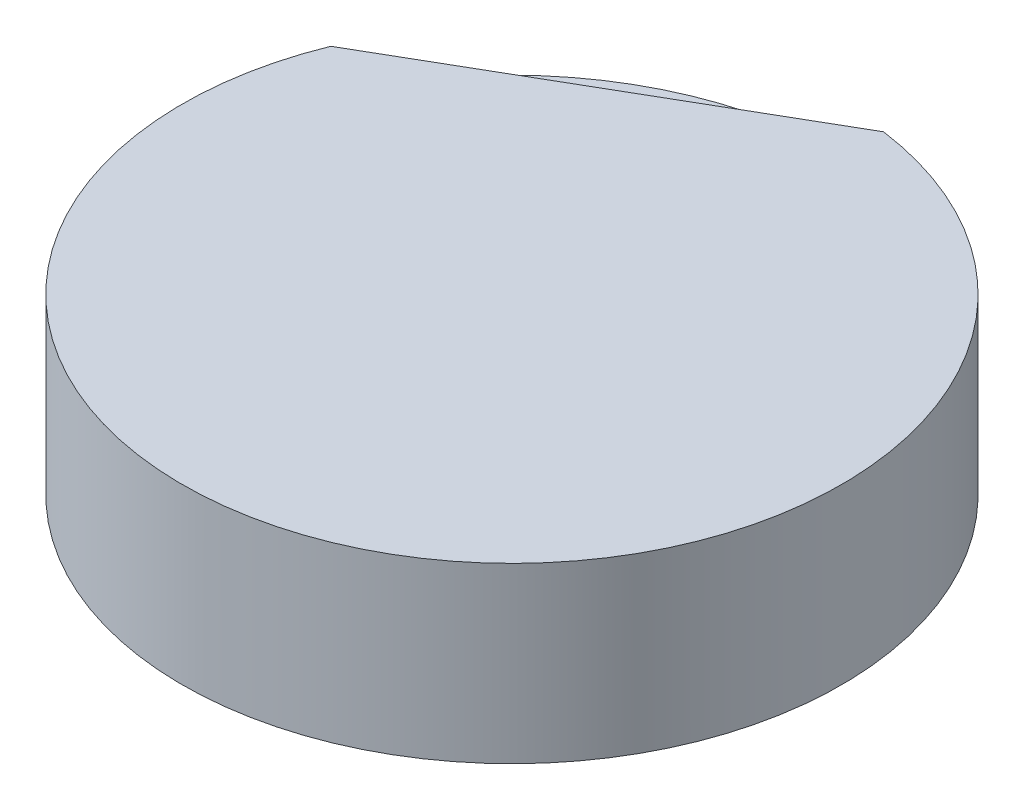
SolidWorks part; units mm, degrees
other "Fixed Steel Cup Liner 3"
ref_plane "Front Plane" through (0, 0, 0) normal (0, 0, 1) x (1, 0, 0)
ref_plane "Top Plane" through (0, 0, 0) normal (0, 1, 0) x (1, 0, 0)
ref_plane "Right Plane" through (0, 0, 0) normal (1, 0, 0) x (0, 0, -1)
sketch3d "Keyed Back Sketch datum points"
  point P0 (-56.2917, -69, 0)
  point P1 (-46.2917, -69, 0)
  point P2 (-56.2917, -69, 10)
ref_plane "Keyed Back Sketch plane" through (0, -69, 0) normal (0, -1, 0) x (-1, 0, 0)
sketch "Keyed Back Sketch" plane through (0, -69, 0) normal (0, -1, 0) x (-1, 0, 0)
  line L0 (74.8116, 27.4126) -> (70.7718, 29.745)
  arc A0 (70.7718, 29.745) -> (74.8116, 27.4126) centre (71.2917, 25.9808) ccw
extrude "Keyed Back" add sketch "Keyed Back Sketch" along normal blind 0.5 separate body
sketch3d "Cup Blank Sketch datum points"
  point P0 (-56.2917, -69.5, 0)
  point P1 (-46.2917, -69.5, 0)
  point P2 (-56.2917, -69.5, 10)
ref_plane "Cup Blank Sketch plane" through (0, -69.5, 0) normal (0, -1, 0) x (-1, 0, 0)
sketch "Cup Blank Sketch" plane through (0, -69.5, 0) normal (0, -1, 0) x (-1, 0, 0)
  circle A0 centre (71.2917, 25.9808) radius 3.8
extrude "Cup Blank" add sketch "Cup Blank Sketch" along normal blind 1.5
sketch3d "Spherical Bearing Seat axis line"
  line L0 (-71.2917, -73, -35.9808) -> (-71.2917, -73, -15.9808) construction
ref_axis "Spherical Bearing Seat axis" through (-71.2917, -73, -35.9808) along (0, 0, 1)
sketch3d "Spherical Bearing Seat profile datum points"
  point P0 (-71.2917, -73, -25.9808)
  point P1 (-61.2917, -73, -25.9808)
  point P2 (-71.2917, -73, -15.9808)
ref_plane "Spherical Bearing Seat profile plane" through (0, -73, 0) normal (0, -1, 0) x (-1, 0, 0)
sketch "Spherical Bearing Seat profile" plane through (0, -73, 0) normal (0, -1, 0) x (-1, 0, 0)
  line L0 (71.2917, 22.8808) -> (71.2917, 29.0808)
  arc A0 (71.2917, 29.0808) -> (71.2917, 22.8808) centre (71.2917, 25.9808) ccw
revolve "Spherical Bearing Seat" cut sketch "Spherical Bearing Seat profile" angle 360 about axis through (-71.2917, -73, -35.9808) along (0, 0, 1)
